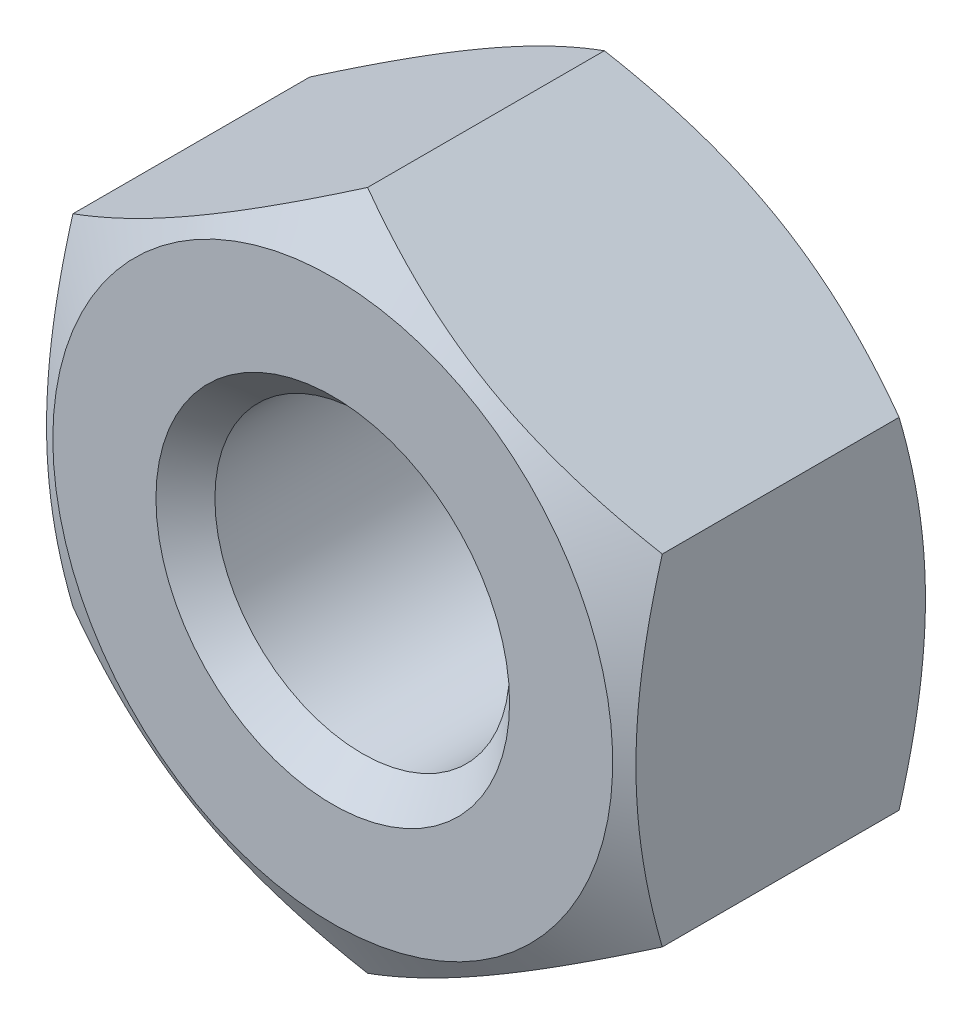
SolidWorks part; units mm, degrees
ref_plane "Спереди" through (0, 0, 0) normal (0, 0, 1) x (1, 0, 0)
ref_plane "Сверху" through (0, 0, 0) normal (0, 1, 0) x (1, 0, 0)
ref_plane "Справа" through (0, 0, 0) normal (1, 0, 0) x (0, 0, -1)
other "Configuration Table"
sketch "Эскиз1" plane through (0, 0, 0) normal (0, 0, 1) x (1, 0, 0)
  line L1 (0, 5.7735) -> (-5, 2.8868)
  line L2 (-5, 2.8868) -> (-5, -2.8868)
  line L3 (-5, -2.8868) -> (0, -5.7735)
  line L4 (0, -5.7735) -> (5, -2.8868)
  line L5 (5, -2.8868) -> (5, 2.8868)
  line L6 (5, 2.8868) -> (0, 5.7735)
  circle A0 centre (0, 0) radius 5 construction
  circle A1 centre (0, 0) radius 2.5
  dimension "D2" = 5
  dimension "D1" = 10
extrude "Бобышка-Вытянуть1" add sketch "Эскиз1" along normal blind 5.2
cosmetic thread "Условное изображение резьбы1" parameters "D2"=6
sketch "Эскиз2" plane through (0, 0, 0) normal (1, 0, 0) x (0, 0, -1)
  line L0 (0, 5.7735) -> (-0.5909, 5.7735)
  line L1 (-5.2, 5.7735) -> (0, 5.7735) construction
  line L2 (-0.5909, 5.7735) -> (0, 4.75)
  line L3 (0, 2.8868) -> (0, 5.7735) construction
  line L4 (0, 4.75) -> (0, 5.7735)
  line L5 (0, 0) -> (-5.2, 0) construction
  line L6 (0, -2.8868) -> (0, 2.8868) construction
  line L7 (-5.2, -2.8868) -> (-5.2, 2.8868) construction
  line L8 (-2.6, 0) -> (-2.6, 6.7597) construction
  line L9 (-5.2, 4.75) -> (-5.2, 5.7735)
  line L10 (-4.6091, 5.7735) -> (-5.2, 4.75)
  line L11 (-5.2, 5.7735) -> (-4.6091, 5.7735)
  dimension "D1" = 30
  dimension "D2" = 9.5
revolve "Вырез-Повернуть1" cut sketch "Эскиз2" angle 360 about L5
chamfer "Фаска1" distance 0.5 angle 45 2 edges at (2.5, 0, 5.2) (2.5, 0, 0)
